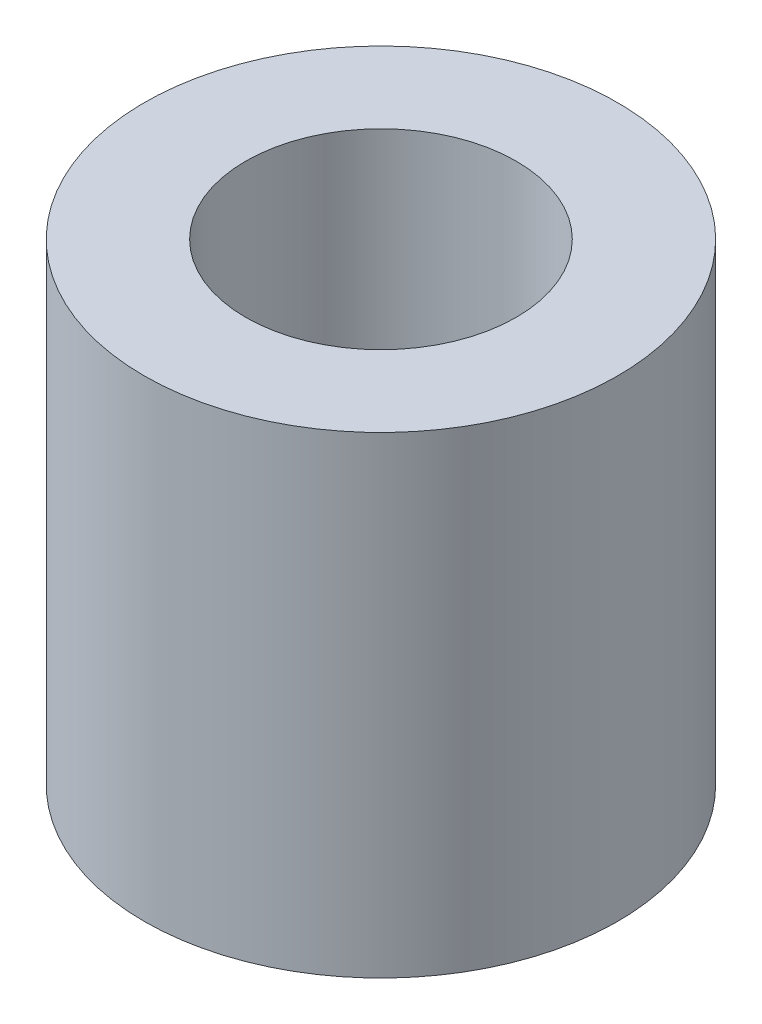
SolidWorks part; units mm, degrees
ref_plane "Front" through (0, 0, 0) normal (0, 0, 1) x (1, 0, 0)
ref_plane "Top" through (0, 0, 0) normal (0, 1, 0) x (1, 0, 0)
ref_plane "Right" through (0, 0, 0) normal (1, 0, 0) x (0, 0, -1)
sketch "Sketch2" plane through (0, 0, 0) normal (0, 1, 0) x (1, 0, 0)
  circle A0 centre (0, 0) radius 5.335
  circle A1 centre (0, 0) radius 3.05
  dimension "D1" = 10.67
  dimension "D2" = 6.1
extrude "Boss-Extrude1" add sketch "Sketch2" along normal blind 10.65
